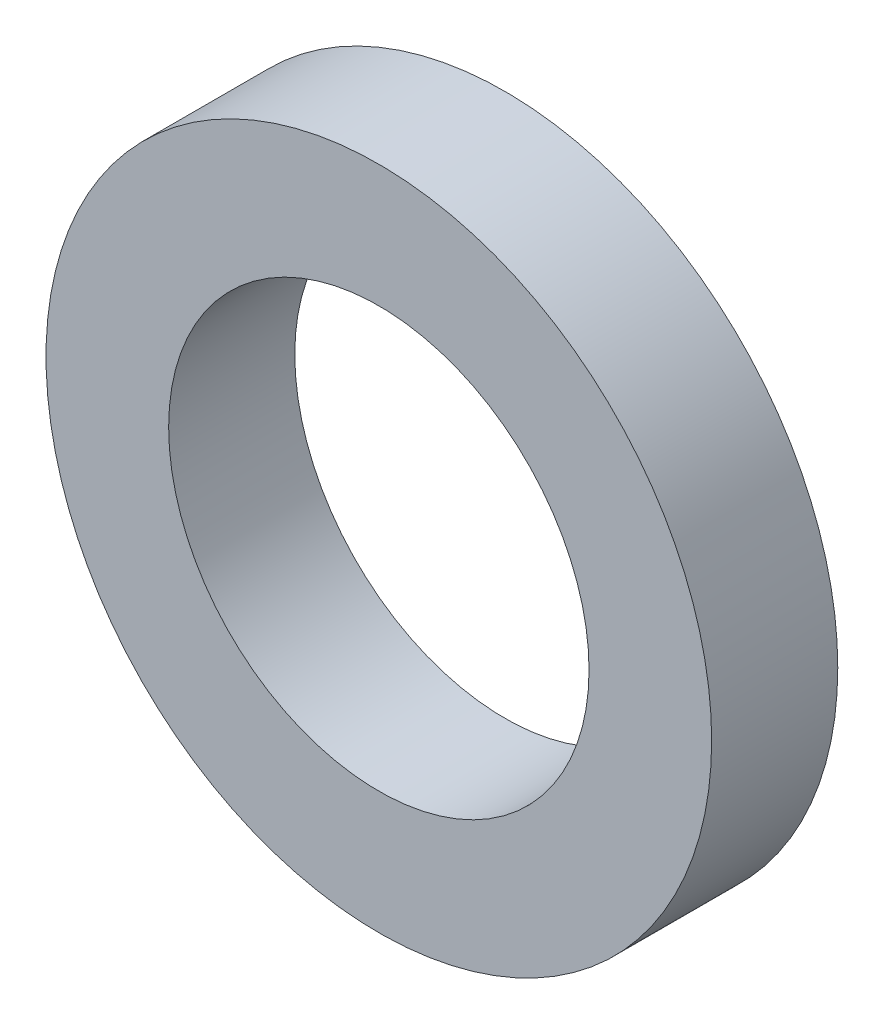
SolidWorks part; units mm, degrees
ref_plane "Front" through (0, 0, 0) normal (0, 0, 1) x (1, 0, 0)
ref_plane "Top" through (0, 0, 0) normal (0, 1, 0) x (1, 0, 0)
ref_plane "Right" through (0, 0, 0) normal (1, 0, 0) x (0, 0, -1)
sketch "Skizze1" plane through (0, 0, 0) normal (0, 0, 1) x (1, 0, 0)
  circle A0 centre (0, 0) radius 30
  circle A1 centre (0, 0) radius 47.5
  dimension "D1" = 60
  dimension "D2" = 95
extrude "Aufsatz-Linear austragen1" add sketch "Skizze1" along normal blind 18
